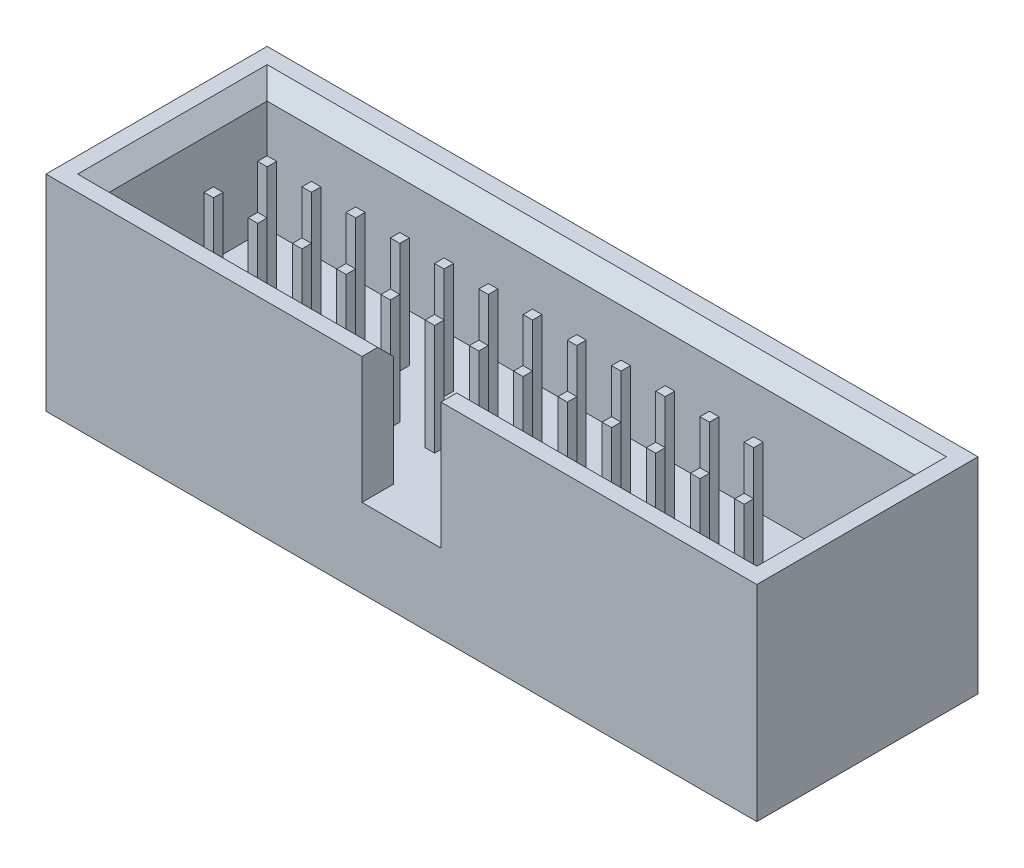
SolidWorks part; units mm, degrees
ref_plane "Front Plane" through (0, 0, 0) normal (0, 0, 1) x (1, 0, 0)
ref_plane "Top Plane" through (0, 0, 0) normal (0, 1, 0) x (1, 0, 0)
ref_plane "Right Plane" through (0, 0, 0) normal (1, 0, 0) x (0, 0, -1)
sketch "Sketch1" plane through (0, 0, 0) normal (0, 1, 0) x (1, 0, 0)
  line L1 (-11.25, -3.5) -> (11.25, -3.5)
  line L2 (-11.25, -3.5) -> (-11.25, 3.5)
  line L3 (-11.25, 3.5) -> (11.25, 3.5)
  line L4 (11.25, -3.5) -> (11.25, 3.5)
  line L5 (-11.25, -3.5) -> (11.25, 3.5) construction
  line L6 (-11.25, 3.5) -> (11.25, -3.5) construction
  point P0 (0, 0)
  dimension "D1" = 7
  dimension "D2" = 22.5
extrude "Base" add sketch "Sketch1" along normal blind 2.5
sketch "Sketch2" plane through (0, 2.5, 0) normal (0, 1, 0) x (1, 0, 0)
  line L0 (-1.25, -2.5) -> (-1.25, -3.5)
  line L1 (-11.25, -3.5) -> (11.25, -3.5) construction
  line L2 (-1.25, -3.5) -> (-11.25, -3.5)
  line L3 (-11.25, -3.5) -> (-11.25, 3.5)
  line L4 (-11.25, 3.5) -> (11.25, 3.5)
  line L5 (11.25, 3.5) -> (-11.25, 3.5) construction
  line L6 (11.25, -3.5) -> (11.25, 3.5) construction
  line L7 (11.25, 3.5) -> (11.25, -3.5)
  line L8 (11.25, -3.5) -> (1.25, -3.5)
  line L9 (1.25, -3.5) -> (1.25, -2.5)
  line L10 (1.25, -2.5) -> (10.25, -2.5)
  line L11 (10.25, -2.5) -> (10.25, 2.5)
  line L12 (10.25, 2.5) -> (-10.25, 2.5)
  line L13 (-10.25, 2.5) -> (-10.25, -2.5)
  line L14 (-10.25, -2.5) -> (-1.25, -2.5)
  dimension "D1" = 1
  dimension "D2" = 1
  dimension "D3" = 1
  dimension "D4" = 1
  dimension "D5" = 1
  dimension "D6" = 2.5
  dimension "D7" = 1.25
extrude "rims" add sketch "Sketch2" along normal blind 4
chamfer "Chamfer1" distance 0.5 angle 45 5 edges at (5.75, 6.5, 2.5) (10.25, 6.5, 0) (-5.75, 6.5, 2.5) (-10.25, 6.5, 0) (0, 6.5, -2.5)
sketch "Sketch3" plane through (0, 2.5, 0) normal (0, 1, 0) x (1, 0, 0)
  line L0 (-10.25, -2.5) -> (-10.25, 2.5) construction
  line L1 (-8.75, -1) -> (-8.45, -1)
  line L2 (-8.75, -1) -> (-8.75, -0.7)
  line L3 (-8.75, -0.7) -> (-8.45, -0.7)
  line L4 (-8.45, -1) -> (-8.45, -0.7)
  line L5 (-8.75, -1) -> (-8.45, -0.7) construction
  line L6 (-8.75, -0.7) -> (-8.45, -1) construction
  line L7 (-8.75, 0.7) -> (-8.45, 0.7)
  line L8 (-8.75, 0.7) -> (-8.75, 1)
  line L9 (-8.75, 1) -> (-8.45, 1)
  line L10 (-8.45, 0.7) -> (-8.45, 1)
  line L11 (-8.75, 0.7) -> (-8.45, 1) construction
  line L12 (-8.75, 1) -> (-8.45, 0.7) construction
  line L13 (-1.25, -2.5) -> (-10.25, -2.5) construction
  line L14 (-10.25, 2.5) -> (10.25, 2.5) construction
  line L15 (-7.35, -1) -> (-7.05, -1)
  line L16 (-7.35, -1) -> (-7.35, -0.7)
  line L17 (-7.35, -0.7) -> (-7.05, -0.7)
  line L18 (-7.05, -1) -> (-7.05, -0.7)
  line L19 (-7.35, -1) -> (-7.05, -0.7) construction
  line L20 (-7.35, -0.7) -> (-7.05, -1) construction
  line L21 (-5.95, -1) -> (-5.65, -1)
  line L22 (-5.95, -1) -> (-5.95, -0.7)
  line L23 (-5.95, -0.7) -> (-5.65, -0.7)
  line L24 (-5.65, -1) -> (-5.65, -0.7)
  line L25 (-5.95, -1) -> (-5.65, -0.7) construction
  line L26 (-5.95, -0.7) -> (-5.65, -1) construction
  line L27 (-4.55, -1) -> (-4.25, -1)
  line L28 (-4.55, -1) -> (-4.55, -0.7)
  line L29 (-4.55, -0.7) -> (-4.25, -0.7)
  line L30 (-4.25, -1) -> (-4.25, -0.7)
  line L31 (-4.55, -1) -> (-4.25, -0.7) construction
  line L32 (-4.55, -0.7) -> (-4.25, -1) construction
  line L33 (-3.15, -1) -> (-2.85, -1)
  line L34 (-3.15, -1) -> (-3.15, -0.7)
  line L35 (-3.15, -0.7) -> (-2.85, -0.7)
  line L36 (-2.85, -1) -> (-2.85, -0.7)
  line L37 (-3.15, -1) -> (-2.85, -0.7) construction
  line L38 (-3.15, -0.7) -> (-2.85, -1) construction
  line L39 (-1.75, -1) -> (-1.45, -1)
  line L40 (-1.75, -1) -> (-1.75, -0.7)
  line L41 (-1.75, -0.7) -> (-1.45, -0.7)
  line L42 (-1.45, -1) -> (-1.45, -0.7)
  line L43 (-1.75, -1) -> (-1.45, -0.7) construction
  line L44 (-1.75, -0.7) -> (-1.45, -1) construction
  line L45 (-0.35, -1) -> (-0.05, -1)
  line L46 (-0.35, -1) -> (-0.35, -0.7)
  line L47 (-0.35, -0.7) -> (-0.05, -0.7)
  line L48 (-0.05, -1) -> (-0.05, -0.7)
  line L49 (-0.35, -1) -> (-0.05, -0.7) construction
  line L50 (-0.35, -0.7) -> (-0.05, -1) construction
  line L51 (1.05, -1) -> (1.35, -1)
  line L52 (1.05, -1) -> (1.05, -0.7)
  line L53 (1.05, -0.7) -> (1.35, -0.7)
  line L54 (1.35, -1) -> (1.35, -0.7)
  line L55 (1.05, -1) -> (1.35, -0.7) construction
  line L56 (1.05, -0.7) -> (1.35, -1) construction
  line L57 (2.45, -1) -> (2.75, -1)
  line L58 (2.45, -1) -> (2.45, -0.7)
  line L59 (2.45, -0.7) -> (2.75, -0.7)
  line L60 (2.75, -1) -> (2.75, -0.7)
  line L61 (2.45, -1) -> (2.75, -0.7) construction
  line L62 (2.45, -0.7) -> (2.75, -1) construction
  line L63 (3.85, -1) -> (4.15, -1)
  line L64 (3.85, -1) -> (3.85, -0.7)
  line L65 (3.85, -0.7) -> (4.15, -0.7)
  line L66 (4.15, -1) -> (4.15, -0.7)
  line L67 (3.85, -1) -> (4.15, -0.7) construction
  line L68 (3.85, -0.7) -> (4.15, -1) construction
  line L69 (5.25, -1) -> (5.55, -1)
  line L70 (5.25, -1) -> (5.25, -0.7)
  line L71 (5.25, -0.7) -> (5.55, -0.7)
  line L72 (5.55, -1) -> (5.55, -0.7)
  line L73 (5.25, -1) -> (5.55, -0.7) construction
  line L74 (5.25, -0.7) -> (5.55, -1) construction
  line L75 (6.65, -1) -> (6.95, -1)
  line L76 (6.65, -1) -> (6.65, -0.7)
  line L77 (6.65, -0.7) -> (6.95, -0.7)
  line L78 (6.95, -1) -> (6.95, -0.7)
  line L79 (6.65, -1) -> (6.95, -0.7) construction
  line L80 (6.65, -0.7) -> (6.95, -1) construction
  line L81 (8.05, -1) -> (8.35, -1)
  line L82 (8.05, -1) -> (8.05, -0.7)
  line L83 (8.05, -0.7) -> (8.35, -0.7)
  line L84 (8.35, -1) -> (8.35, -0.7)
  line L85 (8.05, -1) -> (8.35, -0.7) construction
  line L86 (8.05, -0.7) -> (8.35, -1) construction
  line L87 (-7.35, 0.7) -> (-7.05, 0.7)
  line L88 (-7.35, 0.7) -> (-7.35, 1)
  line L89 (-7.35, 1) -> (-7.05, 1)
  line L90 (-7.05, 0.7) -> (-7.05, 1)
  line L91 (-7.35, 0.7) -> (-7.05, 1) construction
  line L92 (-7.35, 1) -> (-7.05, 0.7) construction
  line L93 (-5.95, 0.7) -> (-5.65, 0.7)
  line L94 (-5.95, 0.7) -> (-5.95, 1)
  line L95 (-5.95, 1) -> (-5.65, 1)
  line L96 (-5.65, 0.7) -> (-5.65, 1)
  line L97 (-5.95, 0.7) -> (-5.65, 1) construction
  line L98 (-5.95, 1) -> (-5.65, 0.7) construction
  line L99 (-4.55, 0.7) -> (-4.25, 0.7)
  line L100 (-4.55, 0.7) -> (-4.55, 1)
  line L101 (-4.55, 1) -> (-4.25, 1)
  line L102 (-4.25, 0.7) -> (-4.25, 1)
  line L103 (-4.55, 0.7) -> (-4.25, 1) construction
  line L104 (-4.55, 1) -> (-4.25, 0.7) construction
  line L105 (-3.15, 0.7) -> (-2.85, 0.7)
  line L106 (-3.15, 0.7) -> (-3.15, 1)
  line L107 (-3.15, 1) -> (-2.85, 1)
  line L108 (-2.85, 0.7) -> (-2.85, 1)
  line L109 (-3.15, 0.7) -> (-2.85, 1) construction
  line L110 (-3.15, 1) -> (-2.85, 0.7) construction
  line L111 (-1.75, 0.7) -> (-1.45, 0.7)
  line L112 (-1.75, 0.7) -> (-1.75, 1)
  line L113 (-1.75, 1) -> (-1.45, 1)
  line L114 (-1.45, 0.7) -> (-1.45, 1)
  line L115 (-1.75, 0.7) -> (-1.45, 1) construction
  line L116 (-1.75, 1) -> (-1.45, 0.7) construction
  line L117 (-0.35, 0.7) -> (-0.05, 0.7)
  line L118 (-0.35, 0.7) -> (-0.35, 1)
  line L119 (-0.35, 1) -> (-0.05, 1)
  line L120 (-0.05, 0.7) -> (-0.05, 1)
  line L121 (-0.35, 0.7) -> (-0.05, 1) construction
  line L122 (-0.35, 1) -> (-0.05, 0.7) construction
  line L123 (1.05, 0.7) -> (1.35, 0.7)
  line L124 (1.05, 0.7) -> (1.05, 1)
  line L125 (1.05, 1) -> (1.35, 1)
  line L126 (1.35, 0.7) -> (1.35, 1)
  line L127 (1.05, 0.7) -> (1.35, 1) construction
  line L128 (1.05, 1) -> (1.35, 0.7) construction
  line L129 (2.45, 0.7) -> (2.75, 0.7)
  line L130 (2.45, 0.7) -> (2.45, 1)
  line L131 (2.45, 1) -> (2.75, 1)
  line L132 (2.75, 0.7) -> (2.75, 1)
  line L133 (2.45, 0.7) -> (2.75, 1) construction
  line L134 (2.45, 1) -> (2.75, 0.7) construction
  line L135 (3.85, 0.7) -> (4.15, 0.7)
  line L136 (3.85, 0.7) -> (3.85, 1)
  line L137 (3.85, 1) -> (4.15, 1)
  line L138 (4.15, 0.7) -> (4.15, 1)
  line L139 (3.85, 0.7) -> (4.15, 1) construction
  line L140 (3.85, 1) -> (4.15, 0.7) construction
  line L141 (5.25, 0.7) -> (5.55, 0.7)
  line L142 (5.25, 0.7) -> (5.25, 1)
  line L143 (5.25, 1) -> (5.55, 1)
  line L144 (5.55, 0.7) -> (5.55, 1)
  line L145 (5.25, 0.7) -> (5.55, 1) construction
  line L146 (5.25, 1) -> (5.55, 0.7) construction
  line L147 (6.65, 0.7) -> (6.95, 0.7)
  line L148 (6.65, 0.7) -> (6.65, 1)
  line L149 (6.65, 1) -> (6.95, 1)
  line L150 (6.95, 0.7) -> (6.95, 1)
  line L151 (6.65, 0.7) -> (6.95, 1) construction
  line L152 (6.65, 1) -> (6.95, 0.7) construction
  point P0 (-8.6, -0.85)
  point P5 (-8.6, 0.85)
  point P17 (-7.2, -0.85)
  point P22 (-5.8, -0.85)
  point P27 (-4.4, -0.85)
  point P32 (-3, -0.85)
  point P37 (-1.6, -0.85)
  point P42 (-0.2, -0.85)
  point P47 (1.2, -0.85)
  point P52 (2.6, -0.85)
  point P57 (4, -0.85)
  point P62 (5.4, -0.85)
  point P67 (6.8, -0.85)
  point P72 (8.2, -0.85)
  point P78 (-7.2, 0.85)
  point P83 (-5.8, 0.85)
  point P88 (-4.4, 0.85)
  point P93 (-3, 0.85)
  point P98 (-1.6, 0.85)
  point P103 (-0.2, 0.85)
  point P108 (1.2, 0.85)
  point P113 (2.6, 0.85)
  point P118 (4, 0.85)
  point P123 (5.4, 0.85)
  point P128 (6.8, 0.85)
  dimension "D1" = 0.3
  dimension "D2" = 0.3
  dimension "D3" = 0.3
  dimension "D4" = 1.5
  dimension "D5" = 1.5
  dimension "D6" = 1.5
  dimension "D7" = 1.5
  dimension "D8" = 13
  dimension "D9" = 12
extrude "Boss-Extrude3" add sketch "Sketch3" along normal blind 3.5
